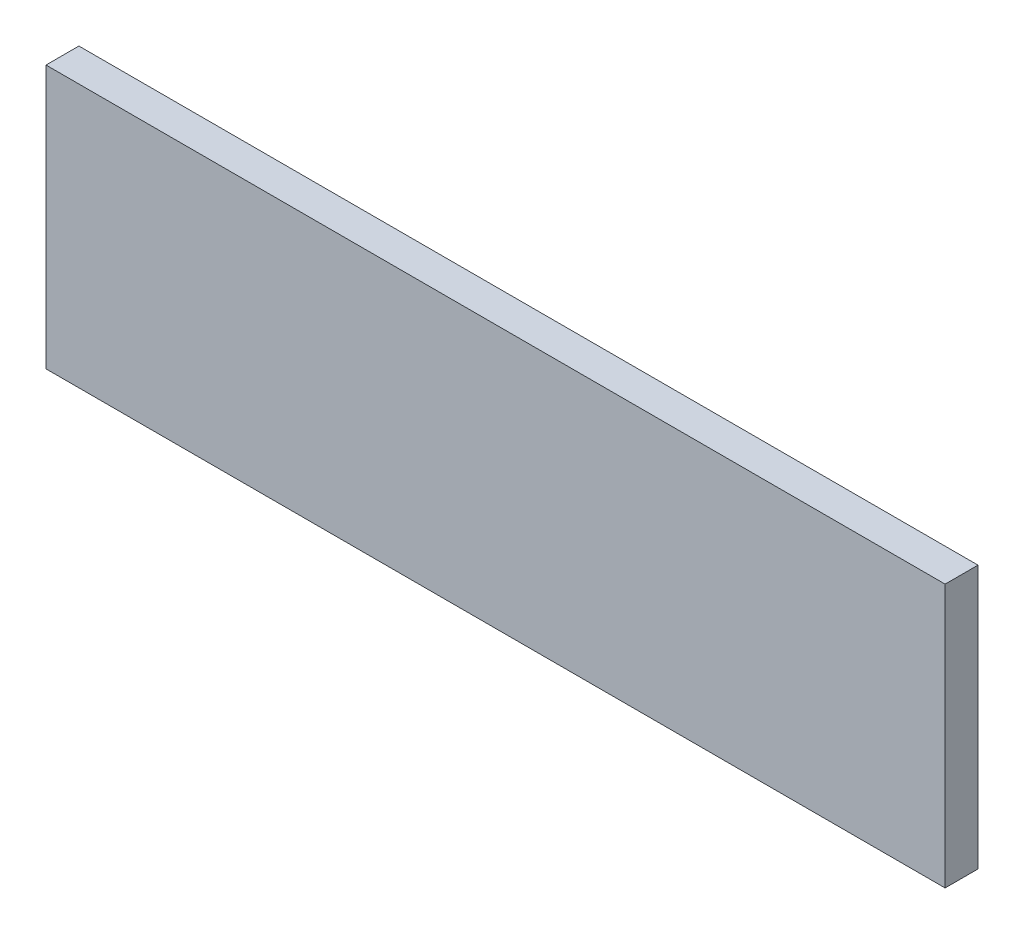
SolidWorks part; units mm, degrees
ref_plane "前视基准面" through (0, 0, 0) normal (0, 0, 1) x (1, 0, 0)
ref_plane "上视基准面" through (0, 0, 0) normal (0, 1, 0) x (1, 0, 0)
ref_plane "右视基准面" through (0, 0, 0) normal (1, 0, 0) x (0, 0, -1)
sketch "草图1" plane through (0, 0, 0) normal (0, 0, 1) x (1, 0, 0)
  line L1 (-205, 60) -> (205, 60)
  line L2 (-205, 60) -> (-205, -60)
  line L3 (-205, -60) -> (205, -60)
  line L4 (205, 60) -> (205, -60)
  line L5 (-205, 60) -> (205, -60) construction
  line L6 (-205, -60) -> (205, 60) construction
  point P0 (0, 0)
  dimension "D1" = 120
  dimension "D2" = 410
extrude "凸台-拉伸1" add sketch "草图1" along normal blind 15
